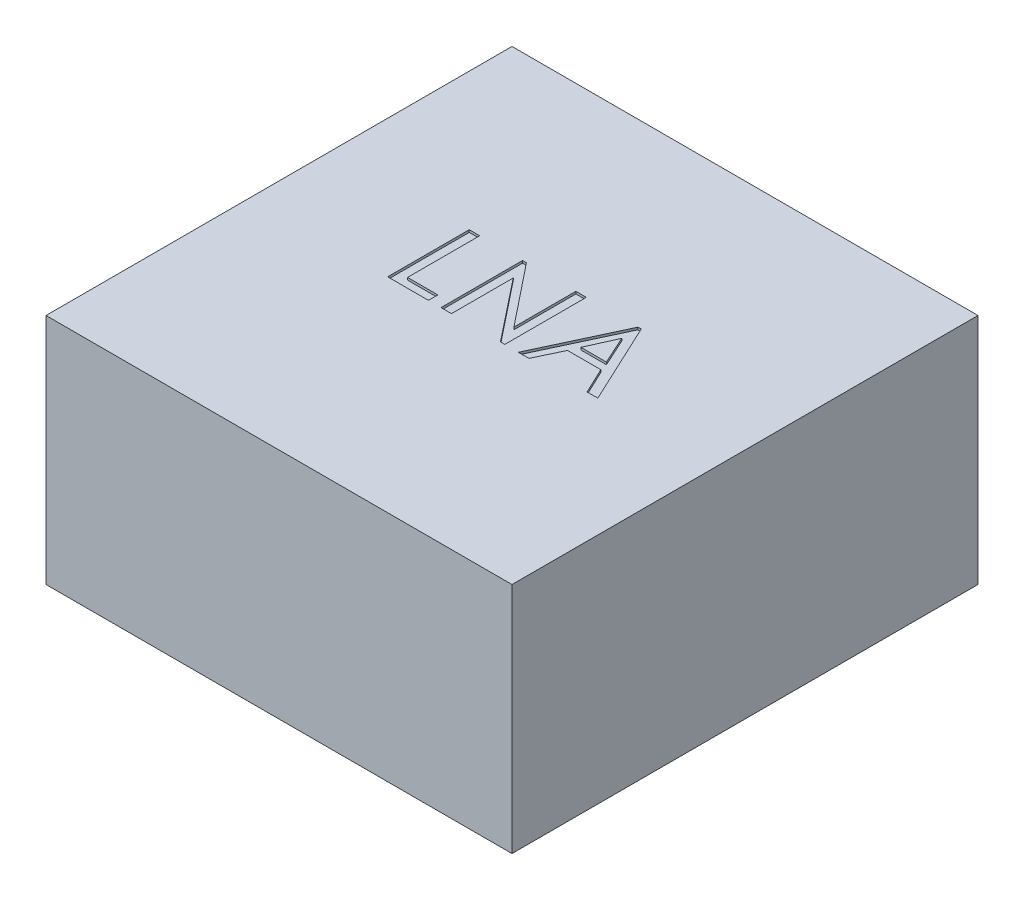
SolidWorks part; units mm, degrees
ref_plane "Front Plane" through (0, 0, 0) normal (0, 0, 1) x (1, 0, 0)
ref_plane "Top Plane" through (0, 0, 0) normal (0, 1, 0) x (1, 0, 0)
ref_plane "Right Plane" through (0, 0, 0) normal (1, 0, 0) x (0, 0, -1)
sketch "Sketch1" plane through (0, 0, 0) normal (0, 1, 0) x (1, 0, 0)
  line L1 (0, 0) -> (20, 0)
  line L2 (0, 0) -> (0, 20)
  line L3 (0, 20) -> (20, 20)
  line L4 (20, 0) -> (20, 20)
  dimension "D1" = 20
  dimension "D2" = 20
extrude "Boss-Extrude1" add sketch "Sketch1" along normal blind 10
sketch "Sketch2" plane through (0, 10, 0) normal (0, 1, 0) x (1, 0, 0)
  text T0 "<b>LNA</b>"
extrude "Cut-Extrude1" cut sketch "Sketch2" against normal blind 0.1
